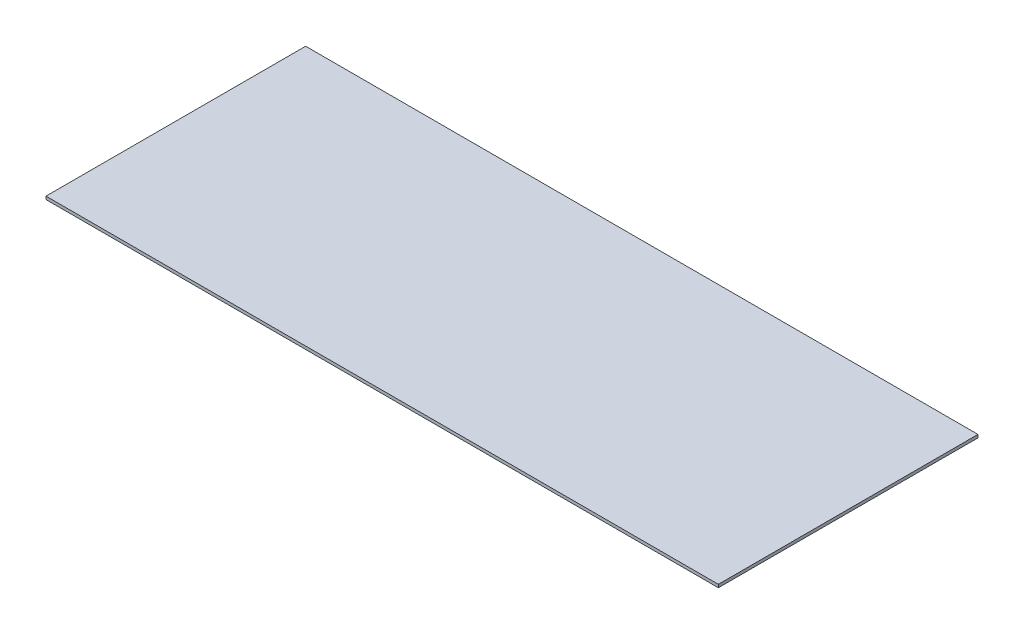
SolidWorks part; units mm, degrees
ref_plane "Front Plane" through (0, 0, 0) normal (0, 0, 1) x (1, 0, 0)
ref_plane "Top Plane" through (0, 0, 0) normal (0, 1, 0) x (1, 0, 0)
ref_plane "Right Plane" through (0, 0, 0) normal (1, 0, 0) x (0, 0, -1)
sketch "Sketch1" plane through (0, 0, 0) normal (0, 1, 0) x (1, 0, 0)
  line L1 (0, 0) -> (448, 0)
  line L2 (0, 0) -> (0, 173)
  line L3 (0, 173) -> (448, 173)
  line L4 (448, 0) -> (448, 173)
  dimension "D1" = 448
  dimension "D2" = 173
extrude "Boss-Extrude1" add sketch "Sketch1" along normal blind 2
